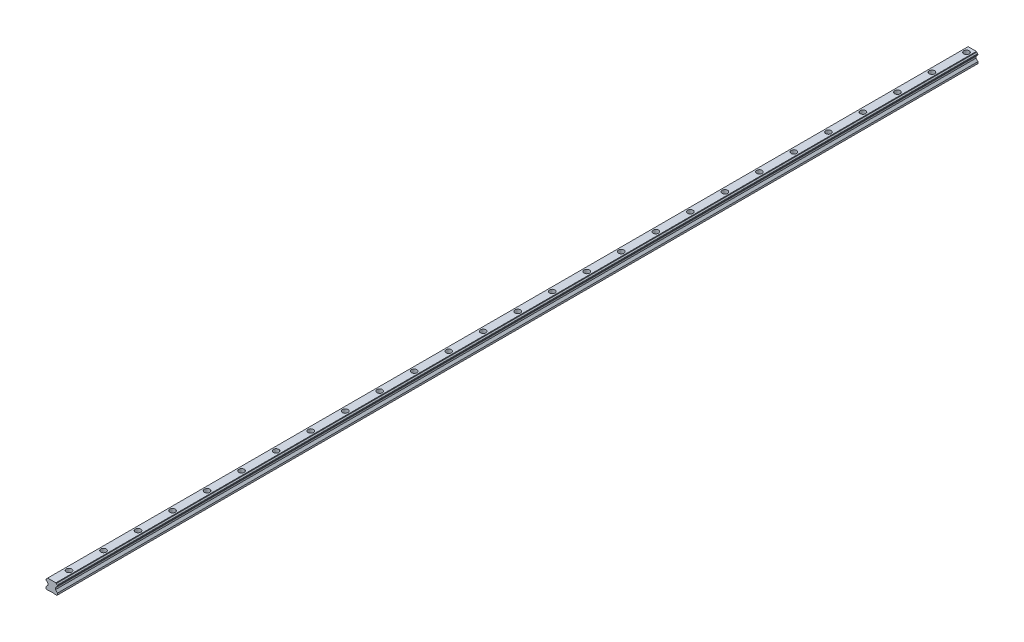
SolidWorks part; units mm, degrees
material "Plain Carbon Steel"
ref_plane "Front Plane" through (0, 0, 0) normal (0, 0, 1) x (1, 0, 0)
ref_plane "Top Plane" through (0, 0, 0) normal (0, 1, 0) x (1, 0, 0)
ref_plane "Right Plane" through (0, 0, 0) normal (1, 0, 0) x (0, 0, -1)
sketch "Sketch1" plane through (0, 0, 0) normal (0, 0, 1) x (1, 0, 0)
  line L0 (-10, -10.4945) -> (-10, -13.4946)
  line L1 (-10, -13.4946) -> (-9, -14.4946)
  line L2 (-9, -14.4946) -> (-3, -14.4946)
  line L3 (-3, -14.4946) -> (-2.5, -13.9946)
  line L4 (-2.5, -13.9946) -> (2.5, -13.9946)
  line L5 (6.55, -7.0447) -> (10, -10.4945)
  line L6 (6.55, -4.1154) -> (6.55, -7.0447)
  line L7 (7.7679, -2.8995) -> (6.55, -4.1154)
  line L8 (10, -0.6654) -> (9.4727, -1.1802)
  line L9 (10, 0.6654) -> (10, -0.6654)
  line L10 (9.4727, 1.1928) -> (10, 0.6654)
  line L11 (7.16, 3.5054) -> (7.7679, 2.8975)
  line L12 (3, -14.4946) -> (2.5, -13.9946)
  line L13 (9, -14.4946) -> (3, -14.4946)
  line L14 (10, -13.4946) -> (9, -14.4946)
  line L15 (10, -10.4945) -> (10, -13.4946)
  line L16 (7.16, 3.5054) -> (-7.16, 3.5054)
  line L17 (-7.16, 3.5054) -> (-7.7679, 2.8975)
  line L18 (-9.4727, 1.1928) -> (-10, 0.6654)
  line L19 (-10, 0.6654) -> (-10, -0.6654)
  line L20 (-10, -0.6654) -> (-9.4727, -1.1802)
  line L21 (-7.7679, -2.8995) -> (-6.55, -4.1154)
  line L22 (-6.55, -4.1154) -> (-6.55, -7.0447)
  line L23 (-6.55, -7.0447) -> (-10, -10.4945)
  line L24 (0, -14.4946) -> (0, -13.9946) construction
  line L25 (0, -13.9946) -> (0, 3.5054) construction
  line L26 (55, 0) -> (-55, 0) construction
  arc A0 (9.4727, -1.1802) -> (7.7679, -2.8995) centre (9.8039, -3.2134) ccw
  arc A1 (7.7679, 2.8975) -> (9.4727, 1.1928) centre (9.8015, 3.2263) ccw
  arc A2 (-7.7679, 2.8975) -> (-9.4727, 1.1928) centre (-9.8015, 3.2263) cw
  arc A3 (-9.4727, -1.1802) -> (-7.7679, -2.8995) centre (-9.8039, -3.2134) cw
  point P38 (10, 0)
  dimension "D17" = 2.06
  dimension "D1" = 20
  dimension "D2" = 1
  dimension "D3" = 1
  dimension "D4" = 0.5
  dimension "D5" = 0.5
  dimension "D6" = 6
  dimension "D7" = 18
  dimension "D8" = 4.0001
  dimension "D9" = 10.55
  dimension "D10" = 13.1001
  dimension "D11" = 15.5359
  dimension "D12" = 0.6079
  dimension "D13" = 0.6079
  dimension "D14" = 17.5
  dimension "D15" = 0.5273
  dimension "D16" = 0.5273
  dimension "D18" = 1.2159
  dimension "D19" = 0.5148
  dimension "D20" = 6.4049
  dimension "D21" = 2.84
  dimension "D22" = 4.1708
extrude "Boss-Extrude1" add sketch "Sketch1" against normal mid plane 1600
sketch "Sketch2" plane through (0, 0, 0) normal (1, 0, 0) x (0, 0, -1)
  line L0 (-770, 3.5054) -> (-770, -14.4946)
  line L1 (800, 3.5054) -> (-800, 3.5054) construction
  line L2 (800, -14.4946) -> (-800, -14.4946) construction
  line L3 (-770, -14.4946) -> (-773, -14.4946)
  line L4 (-773, -14.4946) -> (-773, -4.9946)
  line L5 (-773, -4.9946) -> (-774.75, -4.9946)
  line L6 (-774.75, -4.9946) -> (-774.75, 3.5054)
  line L7 (-774.75, 3.5054) -> (-770, 3.5054)
  line L8 (-800, -7.0447) -> (-800, -4.1154) construction
  point P12 (-800, -5.58)
  dimension "D1" = 3
  dimension "D2" = 4.75
  dimension "D3" = 8.5
  dimension "D4" = 30
revolve "Cut-Revolve1" cut sketch "Sketch2" angle 360 about L0
pattern_linear "LPattern1" count 27 spacing 60 along (0, 0, -1) of "Cut-Revolve1"
